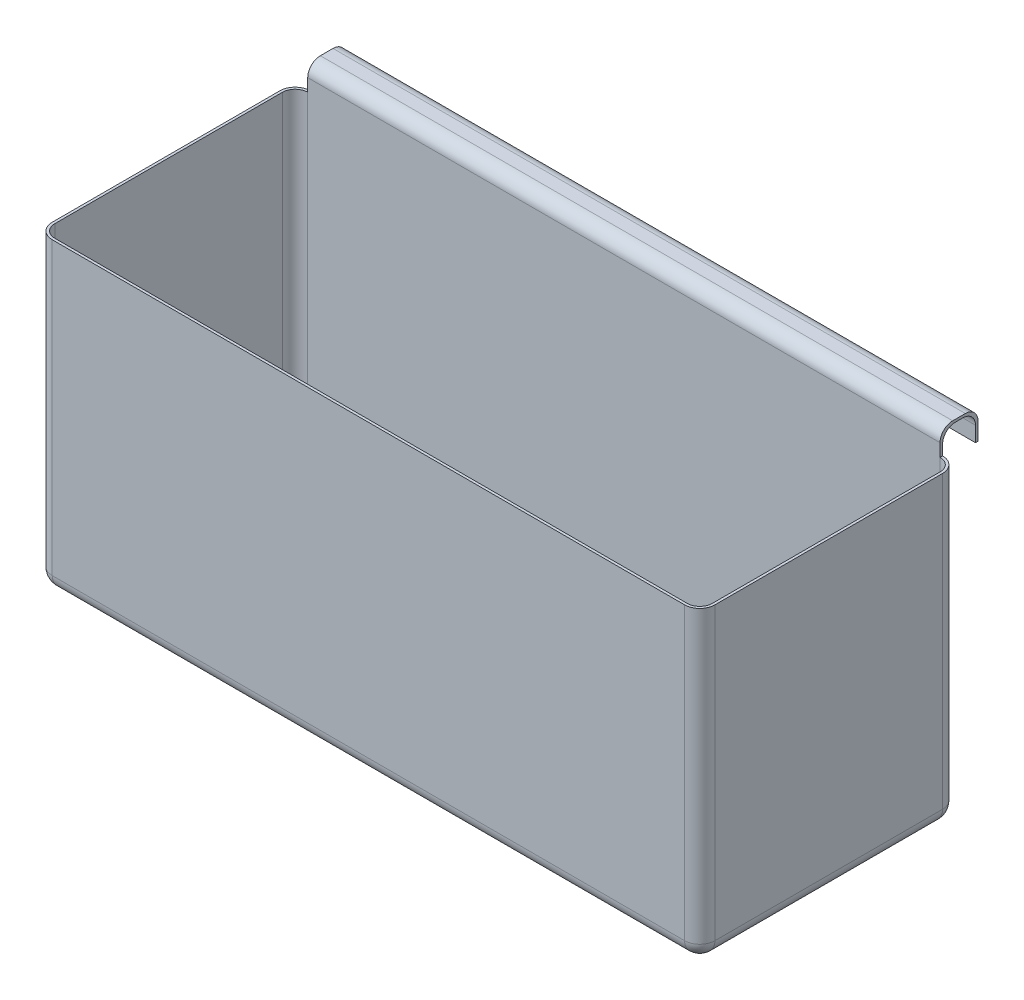
SolidWorks part; units mm, degrees
ref_plane "Front Plane" through (0, 0, 0) normal (0, 0, 1) x (1, 0, 0)
ref_plane "Top Plane" through (0, 0, 0) normal (0, 1, 0) x (1, 0, 0)
ref_plane "Right Plane" through (0, 0, 0) normal (1, 0, 0) x (0, 0, -1)
sketch "Sketch1" plane through (0, 0, 0) normal (0, 1, 0) x (1, 0, 0)
  line L1 (130, -50) -> (-130, -50)
  line L2 (130, -50) -> (130, 50)
  line L3 (130, 50) -> (-130, 50)
  line L4 (-130, -50) -> (-130, 50)
  line L5 (130, -50) -> (-130, 50) construction
  line L6 (130, 50) -> (-130, -50) construction
  point P0 (0, 0)
  dimension "D1" = 260
  dimension "D2" = 100
extrude "Boss-Extrude1" add sketch "Sketch1" against normal blind 120
fillet "Fillet1" radius 5 8 edges at (0, -120, 50) (130, -120, 0) (0, -120, -50) (-130, -120, 0) (-130, -60, 50) (-130, -60, -50) (130, -60, -50) (130, -60, 50)
shell "Shell1" thickness 1
sketch "Sketch2" plane through (0, 0, 0) normal (1, 0, 0) x (0, 0, -1)
  line L0 (51, 0) -> (51, 4)
  line L1 (56, 9) -> (59, 9)
  line L2 (64, 4) -> (64, -2)
  line L3 (64, -2) -> (65, -2)
  line L4 (65, -2) -> (65, 5)
  line L5 (60, 10) -> (55, 10)
  line L6 (50, 5) -> (50, 0)
  line L7 (50, 0) -> (51, 0)
  arc A0 (65, 5) -> (60, 10) centre (60, 5) ccw
  arc A1 (50, 5) -> (55, 10) centre (55, 5) cw
  arc A2 (64, 4) -> (59, 9) centre (59, 4) ccw
  arc A3 (56, 9) -> (51, 4) centre (56, 4) ccw
  point P13 (65, 10)
  point P16 (50, 10)
  dimension "D6" = 5
  dimension "D1" = 10
  dimension "D2" = 1
  dimension "D3" = 1
  dimension "D4" = 15
  dimension "D5" = 12
sketch "Sketch3" plane through (0, 0, 0) normal (0, 1, 0) x (1, 0, 0)
  line L0 (-125, 51) -> (125, 51)
sweep "Sweep1" add profiles "Sketch2" path "Sketch3"
